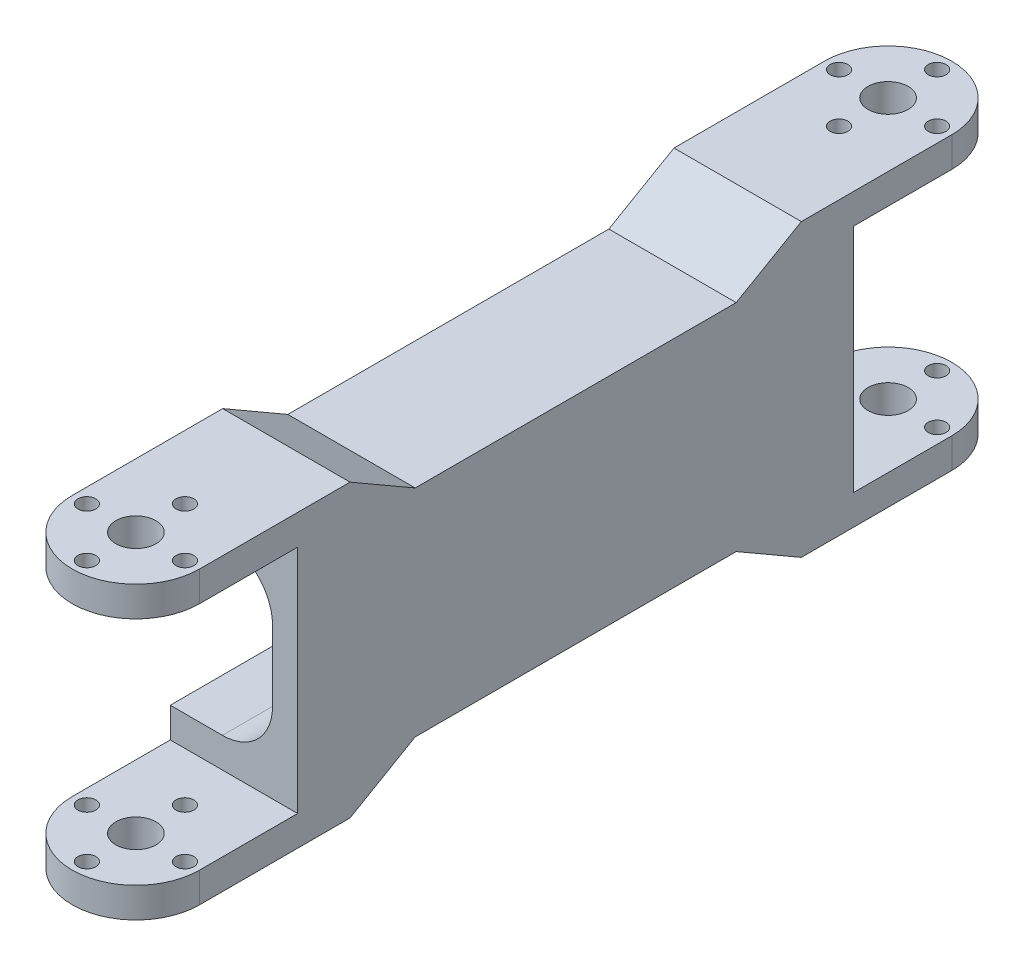
SolidWorks part; units mm, degrees
material "POM Acetal Copolymer"
ref_plane "Front Plane" through (0, 0, 0) normal (0, 0, 1) x (1, 0, 0)
ref_plane "Top Plane" through (0, 0, 0) normal (0, 1, 0) x (1, 0, 0)
ref_plane "Right Plane" through (0, 0, 0) normal (1, 0, 0) x (0, 0, -1)
sketch "Sketch1" plane through (0, 0, 0) normal (0, 1, 0) x (1, 0, 0)
  line L0 (0, 75) -> (0, -75) construction
  line L2 (-12.7, 75) -> (-12.7, -75)
  line L4 (12.7, 75) -> (12.7, -75)
  arc A0 (12.7, 75) -> (-12.7, 75) centre (0, 75) ccw
  arc A1 (-12.7, -75) -> (12.7, -75) centre (0, -75) ccw
  point P5 (0, 0)
  dimension "D1" = 150
  dimension "D2" = 25.4
extrude "Boss-Extrude1" add sketch "Sketch1" along normal mid plane 58
sketch "Sketch3" plane through (-12.7, 0, 0) normal (-1, 0, 0) x (0, 0, 1)
  line L0 (-45, 29) -> (-32.0096, 21.5)
  line L1 (-75, 29) -> (75, 29) construction
  line L2 (-32.0096, 21.5) -> (32.0096, 21.5)
  line L3 (32.0096, 21.5) -> (45, 29)
  line L4 (45, 29) -> (-45, 29)
  line L5 (-75, 29) -> (-75, -29) construction
  point P6 (0, 21.5)
  point P7 (0, 29)
  dimension "D1" = 7.5
  dimension "D2" = 30
  dimension "D3" = 30
extrude "Cut-Extrude1" cut sketch "Sketch3" against normal through all both and the other way through all
mirror "Mirror1" about plane through (0, 0, 0) normal (0, 1, 0) of "Cut-Extrude1"
sketch "Sketch4" plane through (-12.7, 0, 0) normal (-1, 0, 0) x (0, 0, 1)
  line L0 (-87.7, 29) -> (-87.7, -29) construction
  line L1 (55.45, 23) -> (87.7, 23)
  line L2 (-87.7, 23) -> (-55.45, 23)
  line L3 (-87.7, 23) -> (-87.7, 17)
  line L4 (-87.7, 17) -> (-55.45, 17)
  line L5 (-55.45, 23) -> (-55.45, 17)
  line L6 (-87.7, -23) -> (-55.45, -23)
  line L7 (-87.7, -23) -> (-87.7, -17)
  line L8 (-87.7, -17) -> (-55.45, -17)
  line L9 (-55.45, -23) -> (-55.45, -17)
  line L10 (55.45, 23) -> (55.45, 17)
  line L11 (55.45, 17) -> (87.7, 17)
  line L12 (87.7, 23) -> (87.7, 17)
  line L13 (55.45, -17) -> (87.7, -17)
  line L14 (55.45, -17) -> (55.45, -23)
  line L15 (55.45, -23) -> (87.7, -23)
  line L16 (87.7, -17) -> (87.7, -23)
  line L18 (87.7, -29) -> (87.7, 29) construction
  line L19 (-55.45, 17) -> (-55.45, -17) construction
  line L20 (55.45, 17) -> (55.45, -17) construction
  point P20 (-55.45, 0)
  dimension "D1" = 32.25
  dimension "D2" = 6
  dimension "D3" = 34
extrude "Cut-Extrude2" cut sketch "Sketch4" against normal through all both
sketch "Sketch5" plane through (-12.7, 0, 0) normal (-1, 0, 0) x (0, 0, 1)
  line L1 (-87.7, 17) -> (87.7, 17)
  line L2 (-87.7, 17) -> (-87.7, -17)
  line L3 (-87.7, -17) -> (87.7, -17)
  line L4 (87.7, 17) -> (87.7, -17)
extrude "Cut-Extrude3" cut sketch "Sketch5" against normal offset from surface (20.4 mm away) 5 up to face at (12.7, 0, 0)
sketch "Sketch6" plane through (7.7, 0, 0) normal (-1, 0, 0) x (0, 0, 1)
  line L0 (55.45, -17) -> (-55.45, -17) construction
  line L1 (85.0995, 17) -> (55.45, 17)
  line L2 (85.0995, 17) -> (85.0995, -17)
  line L3 (85.0995, -17) -> (55.45, -17)
  line L4 (55.45, 17) -> (55.45, -17)
  line L5 (55.45, -17) -> (55.45, -23) construction
extrude "Cut-Extrude4" cut sketch "Sketch6" against normal through all
sketch "Sketch7" plane through (7.7, 0, 0) normal (-1, 0, 0) x (0, 0, 1)
  line L1 (-85.0995, 17) -> (-55.45, 17)
  line L2 (-85.0995, 17) -> (-85.0995, -17)
  line L3 (-85.0995, -17) -> (-55.45, -17)
  line L4 (-55.45, 17) -> (-55.45, -17)
extrude "Cut-Extrude5" cut sketch "Sketch7" against normal through all
hole_wizard "5/32 (0.14) Diameter Hole1" positions "Sketch11" profile "Sketch12" hole size "5/32" standard "ANSI Inch" end condition through all
sketch "Sketch11" plane through (0, 29, 0) normal (0, 1, 0) x (1, 0, 0)
  line L0 (9.779, -75) -> (-9.779, -75) construction
  line L2 (0, -65.221) -> (0, -84.779) construction
  point P0 (0, -65.221)
  point P2 (-9.779, -75)
  point P4 (9.779, -75)
  point P6 (0, -84.779)
  point P17 (0, -75)
  point P18 (0, -75)
  dimension "D1" = 19.558
sketch "Sketch12" plane through (0, 29, 65.221) normal (1, 0, 0) x (0, 0, 1)
  line L0 (0, 0) -> (0, 58)
  line L1 (0, 58) -> (1.778, 58)
  line L2 (1.778, 58) -> (1.778, 0)
  line L5 (1.778, 0) -> (0, 0)
  line L11 (0, -6.35) -> (0, 107.95) construction
  dimension "Thru Hole Dia." = 3.556
  dimension "Thru Hole Depth" = 58
mirror "Mirror3" about plane through (0, 0, 0) normal (0, 0, 1) of "5/32 (0.14) Diameter Hole1"
sketch "Sketch13" plane through (0, -29, 0) normal (0, -1, 0) x (1, 0, 0)
  line L0 (-9.779, -75) -> (9.779, -75) construction
  circle A0 centre (0, -75) radius 4
  dimension "D1" = 8
extrude "Cut-Extrude6" cut sketch "Sketch13" against normal through all both and the other way through all
mirror "Mirror4" about plane through (0, 0, 0) normal (0, 0, 1) of "Cut-Extrude6"
fillet "Fillet1" radius 10 1 edges at (7.7, 17, 0)
fillet "Fillet2" radius 10 1 edges at (7.7, -17, 0)
